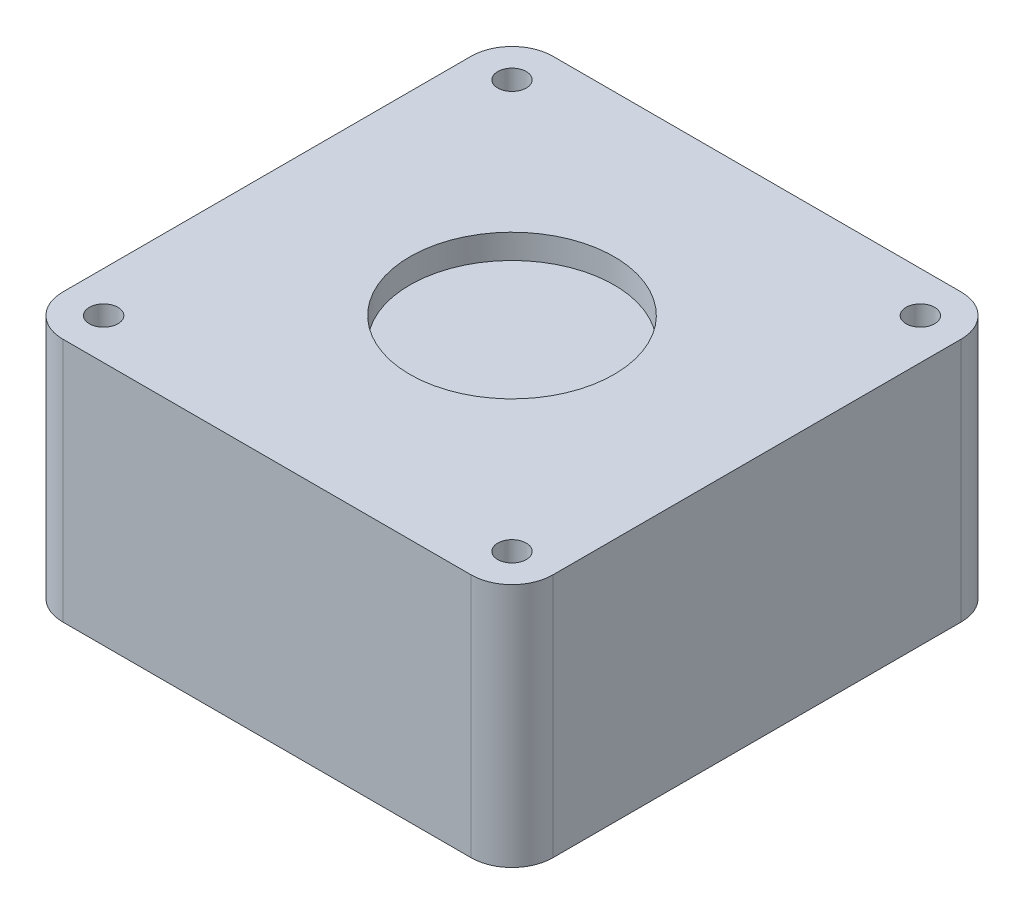
SolidWorks part; units mm, degrees
material "ABS"
ref_plane "前视" through (0, 0, 0) normal (0, 0, 1) x (1, 0, 0)
ref_plane "上视" through (0, 0, 0) normal (0, 1, 0) x (1, 0, 0)
ref_plane "右视" through (0, 0, 0) normal (1, 0, 0) x (0, 0, -1)
sketch "草图1" plane through (0, 0, 0) normal (0, 1, 0) x (1, 0, 0)
  line L1 (-30, -30) -> (30, -30)
  line L2 (-30, -30) -> (-30, 30)
  line L3 (-30, 30) -> (30, 30)
  line L4 (30, -30) -> (30, 30)
  line L5 (-30, -30) -> (30, 30) construction
  line L6 (-30, 30) -> (30, -30) construction
  point P0 (0, 0)
  dimension "D1" = 60
  dimension "D2" = 60
extrude "凸台-拉伸1" add sketch "草图1" along normal blind 30
sketch "草图2" plane through (0, 30, 0) normal (0, 1, 0) x (1, 0, 0)
  line L1 (-25, -25) -> (25, -25) construction
  line L2 (-25, -25) -> (-25, 25) construction
  line L3 (-25, 25) -> (25, 25) construction
  line L4 (25, -25) -> (25, 25) construction
  line L5 (-25, -25) -> (25, 25) construction
  line L6 (-25, 25) -> (25, -25) construction
  circle A0 centre (25, 25) radius 1.75
  circle A1 centre (-25, 25) radius 1.75
  circle A2 centre (-25, -25) radius 1.75
  circle A3 centre (25, -25) radius 1.75
  point P0 (0, 0)
  dimension "D3" = 3.5
  dimension "D4" = 3.5
  dimension "D1" = 50
  dimension "D2" = 50
extrude "切除-拉伸1" cut sketch "草图2" against normal blind 30
sketch "草图3" plane through (0, 30, 0) normal (0, 1, 0) x (1, 0, 0)
  circle A0 centre (0, 0) radius 12.5
  dimension "D1" = 25
extrude "切除-拉伸2" cut sketch "草图3" against normal blind 3
sketch "草图4" plane through (0, 0, 0) normal (0, -1, 0) x (1, 0, 0)
  line L1 (-10, -10) -> (10, -10)
  line L2 (-10, -10) -> (-10, 10)
  line L3 (-10, 10) -> (10, 10)
  line L4 (10, -10) -> (10, 10)
  line L5 (-10, -10) -> (10, 10) construction
  line L6 (-10, 10) -> (10, -10) construction
  point P0 (0, 0)
  dimension "D1" = 20
  dimension "D2" = 20
extrude "切除-拉伸3" cut sketch "草图4" against normal blind 3
fillet "圆角1" radius 5 4 edges at (-30, 15, -30) (30, 15, -30) (30, 15, 30) (-30, 15, 30)
